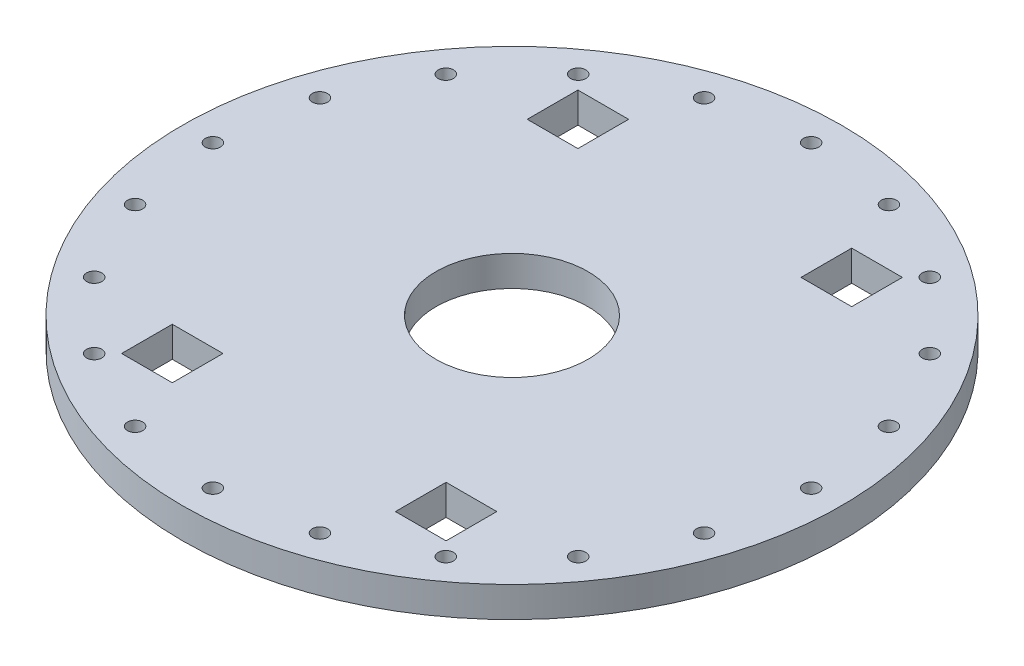
SolidWorks part; units mm, degrees
material "Mahogany"
ref_plane "Front Plane" through (0, 0, 0) normal (0, 0, 1) x (1, 0, 0)
ref_plane "Top Plane" through (0, 0, 0) normal (0, 1, 0) x (1, 0, 0)
ref_plane "Right Plane" through (0, 0, 0) normal (1, 0, 0) x (0, 0, -1)
sketch "Sketch1" plane through (0, 0, 0) normal (0, 1, 0) x (1, 0, 0)
  line L1 (-11, -17.5) -> (-16, -17.5)
  line L2 (-11, -17.5) -> (-11, -22.5)
  line L3 (-11, -22.5) -> (-16, -22.5)
  line L4 (-16, -17.5) -> (-16, -22.5)
  line L5 (-11, -17.5) -> (-16, -22.5) construction
  line L6 (-11, -22.5) -> (-16, -17.5) construction
  line L7 (-11, 22.5) -> (-16, 22.5)
  line L8 (-11, 22.5) -> (-11, 17.5)
  line L9 (-11, 17.5) -> (-16, 17.5)
  line L10 (-16, 22.5) -> (-16, 17.5)
  line L11 (-11, 22.5) -> (-16, 17.5) construction
  line L12 (-11, 17.5) -> (-16, 22.5) construction
  line L13 (16, 22.5) -> (11, 22.5)
  line L14 (16, 22.5) -> (16, 17.5)
  line L15 (16, 17.5) -> (11, 17.5)
  line L16 (11, 22.5) -> (11, 17.5)
  line L17 (16, 22.5) -> (11, 17.5) construction
  line L18 (16, 17.5) -> (11, 22.5) construction
  line L19 (16, -17.5) -> (11, -17.5)
  line L20 (16, -17.5) -> (16, -22.5)
  line L21 (16, -22.5) -> (11, -22.5)
  line L22 (11, -17.5) -> (11, -22.5)
  line L23 (16, -17.5) -> (11, -22.5) construction
  line L24 (16, -22.5) -> (11, -17.5) construction
  circle A0 centre (0, 0) radius 32.5
  circle A1 centre (0, 0) radius 7.5
  point P10 (-13.5, -20)
  point P15 (-13.5, 20)
  point P20 (13.5, 20)
  point P23 (13.5, -20)
  dimension "D1" = 65
  dimension "D2" = 15
  dimension "D3" = 20
  dimension "D4" = 13.5
  dimension "D5" = 5
  dimension "D6" = 5
  dimension "D7" = 5
  dimension "D8" = 5
  dimension "D9" = 20
  dimension "D10" = 13.5
extrude "Boss-Extrude1" add sketch "Sketch1" along normal blind 3
sketch "Sketch2" plane through (0, 0, 0) normal (0, -1, 0) x (1, 0, 0)
  circle A0 centre (0, 0) radius 29.5 construction
  circle A1 centre (0, -29.5) radius 0.75
  circle A2 centre (-9.116, -28.0562) radius 0.75
  circle A3 centre (-17.3397, -23.866) radius 0.75
  circle A4 centre (-23.866, -17.3397) radius 0.75
  circle A5 centre (-28.0562, -9.116) radius 0.75
  circle A6 centre (-29.5, 0) radius 0.75
  circle A7 centre (-28.0562, 9.116) radius 0.75
  circle A8 centre (-23.866, 17.3397) radius 0.75
  circle A9 centre (-17.3397, 23.866) radius 0.75
  circle A10 centre (-9.116, 28.0562) radius 0.75
  circle A11 centre (0, 29.5) radius 0.75
  circle A12 centre (9.116, 28.0562) radius 0.75
  circle A13 centre (17.3397, 23.866) radius 0.75
  circle A14 centre (23.866, 17.3397) radius 0.75
  circle A15 centre (28.0562, 9.116) radius 0.75
  circle A16 centre (29.5, 0) radius 0.75
  circle A17 centre (28.0562, -9.116) radius 0.75
  circle A18 centre (23.866, -17.3397) radius 0.75
  circle A19 centre (17.3397, -23.866) radius 0.75
  circle A20 centre (9.116, -28.0562) radius 0.75
  point P46 (0, 0)
  dimension "D1" = 59
  dimension "D2" = 1.5
  dimension "D3" = 20
extrude "Cut-Extrude1" cut sketch "Sketch2" against normal through all
